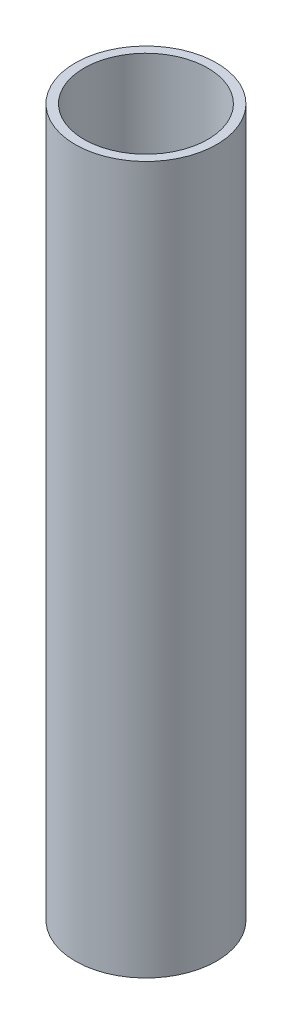
SolidWorks part; units mm, degrees
ref_plane "Front Plane" through (0, 0, 0) normal (0, 0, 1) x (1, 0, 0)
ref_plane "Top Plane" through (0, 0, 0) normal (0, 1, 0) x (1, 0, 0)
ref_plane "Right Plane" through (0, 0, 0) normal (1, 0, 0) x (0, 0, -1)
sketch "Sketch1" plane through (0, 0, 0) normal (0, 1, 0) x (1, 0, 0)
  circle A0 centre (0, 0) radius 12
  dimension "D1" = 24
extrude "Boss-Extrude1" add sketch "Sketch1" along normal blind 120
sketch "Sketch2" plane through (0, 120, 0) normal (0, 1, 0) x (1, 0, 0)
  circle A0 centre (0, 0) radius 10.5
  dimension "D1" = 21
extrude "Cut-Extrude1" cut sketch "Sketch2" against normal blind 20
